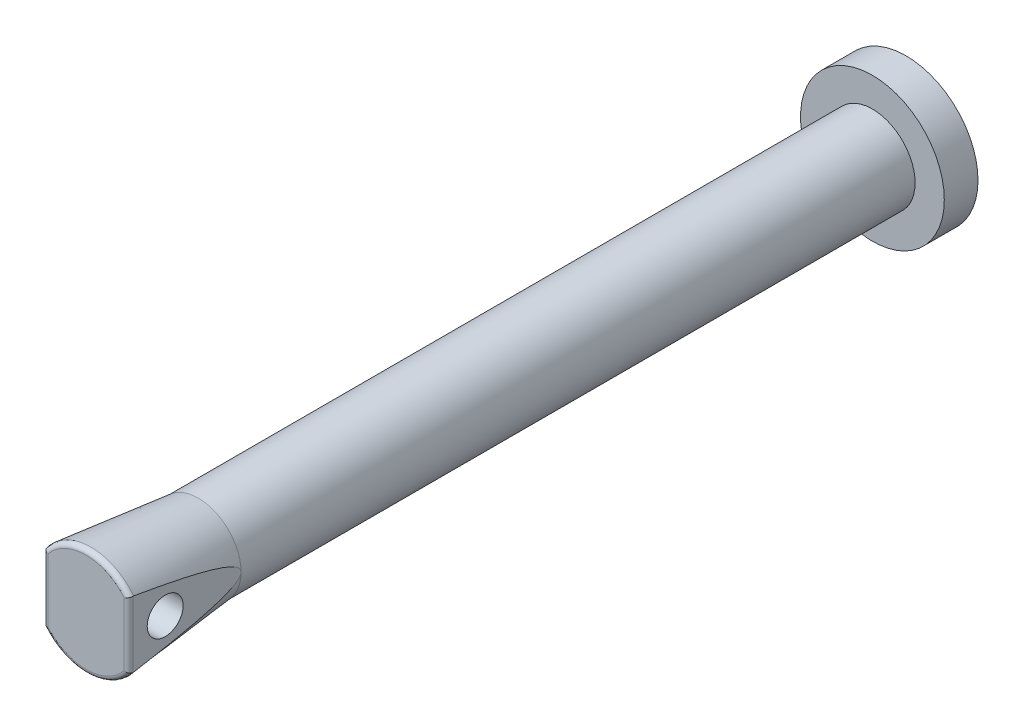
SolidWorks part; units mm, degrees
ref_plane "Спереди" through (0, 0, 0) normal (0, 0, 1) x (1, 0, 0)
ref_plane "Сверху" through (0, 0, 0) normal (0, 1, 0) x (1, 0, 0)
ref_plane "Справа" through (0, 0, 0) normal (1, 0, 0) x (0, 0, -1)
sketch "Эскиз1" plane through (0, 0, 0) normal (0, 0, 1) x (1, 0, 0)
  circle A0 centre (0, 0) radius 3.2
extrude "Вытянуть1" add sketch "Эскиз1" along normal blind 1.5
sketch "Эскиз2" plane through (0, 0, 1.5) normal (0, 0, 1) x (1, 0, 0)
  circle A0 centre (0, 0) radius 1.9
extrude "Вытянуть2" add sketch "Эскиз2" along normal blind 30
sketch "Эскиз4" plane through (0, 0, 31.5) normal (0, 0, 1) x (1, 0, 0)
  circle A0 centre (0, 0) radius 1.9
extrude "Вытянуть3" add sketch "Эскиз4" along normal blind 5 draft 6 draft outward yes
sketch "Эскиз5" plane through (0, 0, 0) normal (0, 1, 0) x (1, 0, 0)
  line L0 (0, -48.5) -> (0, -39.4531) construction
  line L2 (1.9, -49.0898) -> (3.1013, -49.0898)
  line L3 (-1.9, -31.5) -> (-3.1013, -31.5)
  line L4 (-1.9, -31.5) -> (-1.9, -49.0898)
  line L5 (-1.9, -49.0898) -> (-3.1013, -49.0898)
  line L6 (-3.1013, -31.5) -> (-3.1013, -49.0898)
  line L7 (3.1013, -31.5) -> (3.1013, -49.0898)
  line L8 (1.9, -31.5) -> (3.1013, -31.5)
  line L9 (1.9, -31.5) -> (1.9, -49.0898)
extrude "Вытянуть4" cut sketch "Эскиз5" against normal mid plane 35
sketch "Эскиз6" plane through (-1.9, 0, 0) normal (-1, 0, 0) x (0, 0, 1)
  circle A0 centre (34.8773, 0) radius 0.8
extrude "Вытянуть5" cut sketch "Эскиз6" against normal through all
fillet "Скругление1" radius 0.2 4 edges at (0, 2.4255, 36.5) (0, -2.4255, 36.5) (1.9, 0, 36.5) (-1.9, 0, 36.5)
